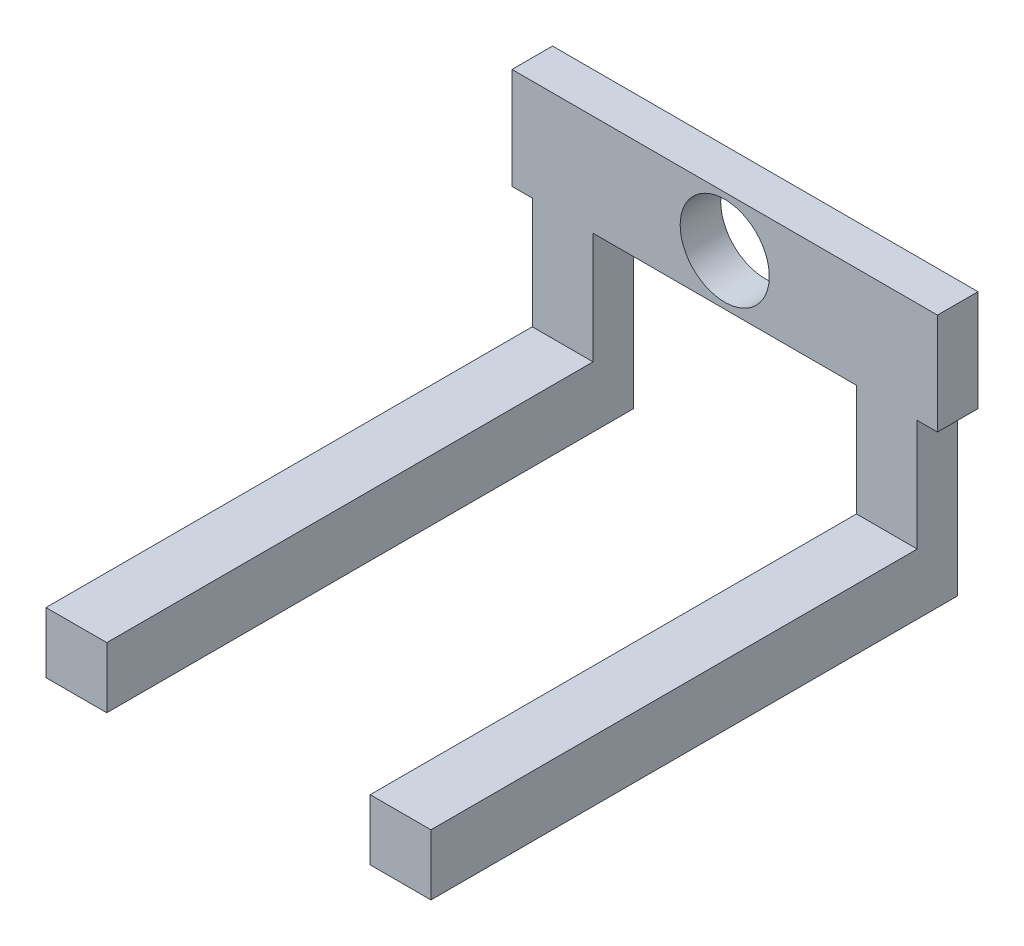
SolidWorks part; units mm, degrees
ref_plane "Ön Düzlem" through (0, 0, 0) normal (0, 0, 1) x (1, 0, 0)
ref_plane "Üst Düzlem" through (0, 0, 0) normal (0, 1, 0) x (1, 0, 0)
ref_plane "Sağ Düzlem" through (0, 0, 0) normal (1, 0, 0) x (0, 0, -1)
sketch "Çizim1" plane through (0, 0, 0) normal (0, 0, 1) x (1, 0, 0)
  line L1 (0, 0) -> (15, 0)
  line L2 (0, 0) -> (0, 15)
  line L3 (0, 15) -> (15, 15)
  line L4 (15, 0) -> (15, 15)
  line L5 (80, 0) -> (95, 0)
  line L6 (80, 0) -> (80, 15)
  line L7 (80, 15) -> (95, 15)
  line L8 (95, 0) -> (95, 15)
  dimension "D1" = 15
  dimension "D2" = 15
  dimension "D3" = 15
  dimension "16" = 15
  dimension "D4" = 65
extrude "Yükseklik-Ekstrüzyon1" add sketch "Çizim1" along normal blind 125
sketch "Çizim2" plane through (0, 0, 0) normal (0, 0, -1) x (-1, 0, 0)
  line L1 (-95, 15) -> (0, 15)
  line L2 (-95, 15) -> (-95, 0)
  line L3 (-95, 0) -> (0, 0)
  line L4 (0, 15) -> (0, 0)
  dimension "D1" = 15
sketch "Çizim3" plane through (0, 0, 0) normal (0, 0, -1) x (-1, 0, 0)
  line L1 (-100, 67.5) -> (5, 67.5)
  line L2 (-100, 67.5) -> (-100, 42.5)
  line L3 (-100, 42.5) -> (-95, 42.5)
  line L4 (5, 67.5) -> (5, 42.5)
  line L5 (-95, 15) -> (-95, 0) construction
  line L6 (0, 15) -> (0, 0) construction
  line L7 (-80, 42.5) -> (-15, 42.5)
  line L8 (-95, 0) -> (-80, 0)
  line L9 (-95, 0) -> (-95, 42.5)
  line L10 (-95, 67.5) -> (-80, 67.5)
  line L11 (-80, 0) -> (-80, 42.5)
  line L12 (-15, 0) -> (0, 0)
  line L13 (-15, 0) -> (-15, 42.5)
  line L14 (-15, 67.5) -> (0, 67.5)
  line L15 (0, 0) -> (0, 42.5)
  line L16 (0, 42.5) -> (5, 42.5)
  point P9 (-100, 55)
  point P21 (0, 0)
  point P22 (0, 0)
  line M6 (-80, 15) -> (-95, 15)
  dimension "D1" = 25
  dimension "D2" = 40
  dimension "15" = 5
  dimension "5" = 5
extrude "Yükseklik-Ekstrüzyon4" add sketch "Çizim3" against normal mid plane 10 contours L15 L16 L4 L1 L2 L3 L9 L11 L7 L13 L12 M6
sketch "Çizim6" plane through (0, 0, -5) normal (0, 0, -1) x (-1, 0, 0)
  line L1 (-95, 15) -> (-80, 15)
  line L2 (-95, 15) -> (-95, 0)
  line L3 (-95, 0) -> (-80, 0)
  line L4 (-80, 15) -> (-80, 0)
extrude "Yükseklik-Ekstrüzyon5" add sketch "Çizim6" against normal up to next
sketch "Çizim7" plane through (0, 0, -5) normal (0, 0, -1) x (-1, 0, 0)
  line L0 (-100, 67.5) -> (5, 67.5) construction
  line L1 (5, 67.5) -> (5, 42.5) construction
  circle A0 centre (-47.5, 55) radius 11
  dimension "D1" = 22
  dimension "D2" = 12.5
  dimension "D3" = 52.5
extrude "Kes-Ekstrüzyon2" cut sketch "Çizim7" against normal blind 53
